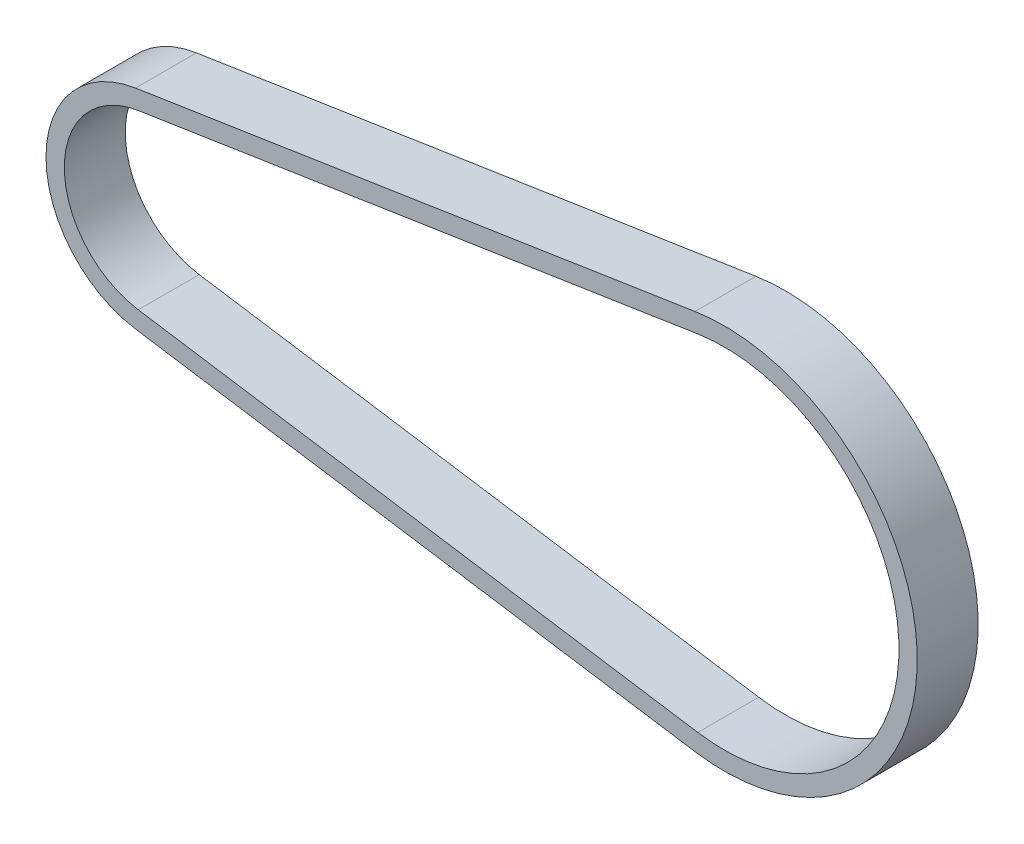
SolidWorks part; units mm, degrees
material "Hexcel AS4C (3000 Filaments)"
ref_plane "Plan de face" through (0, 0, 0) normal (0, 0, 1) x (1, 0, 0)
ref_plane "Plan de dessus" through (0, 0, 0) normal (0, 1, 0) x (1, 0, 0)
ref_plane "Plan de droite" through (0, 0, 0) normal (1, 0, 0) x (0, 0, -1)
sketch "Sketch1" plane through (0, 0, 0) normal (0, 0, 1) x (1, 0, 0)
  line L0 (-47, 0) -> (47, 0) construction
  line L1 (-49.183, 14.1577) -> (42.6339, 28.3154)
  line L2 (-49.183, -14.1577) -> (42.6339, -28.3154)
  line L3 (-49.6402, 17.1226) -> (42.1767, 31.2803)
  line L4 (-49.6402, -17.1226) -> (42.1767, -31.2803)
  arc A0 (42.6339, -28.3154) -> (42.6339, 28.3154) centre (47, 0) ccw
  arc A1 (-49.183, 14.1577) -> (-49.183, -14.1577) centre (-47, 0) ccw
  arc A2 (42.1767, -31.2803) -> (42.1767, 31.2803) centre (47, 0) ccw
  arc A3 (-49.6402, 17.1226) -> (-49.6402, -17.1226) centre (-47, 0) ccw
  point P3 (0, 0)
  dimension "D2" = 57.3
  dimension "D3" = 28.65
  dimension "D1" = 94
  dimension "D4" = 3
extrude "Boss-Extrude1" add sketch "Sketch1" along normal mid plane 10
